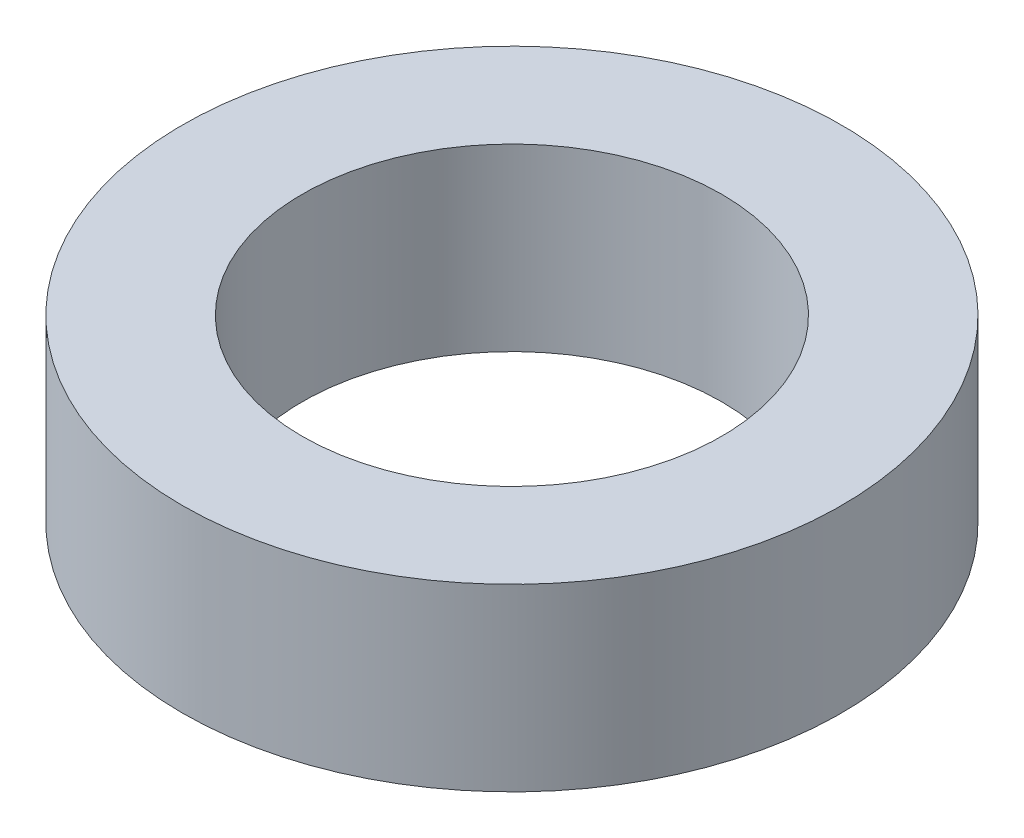
SolidWorks part; units mm, degrees
ref_plane "Front Plane" through (0, 0, 0) normal (0, 0, 1) x (1, 0, 0)
ref_plane "Top Plane" through (0, 0, 0) normal (0, 1, 0) x (1, 0, 0)
ref_plane "Right Plane" through (0, 0, 0) normal (1, 0, 0) x (0, 0, -1)
sketch "Sketch1" plane through (0, 0, 0) normal (0, 1, 0) x (1, 0, 0)
  circle A0 centre (0, 0) radius 5.5
  circle A1 centre (0, 0) radius 3.5
  dimension "D1" = 11
  dimension "D2" = 7
extrude "Boss-Extrude1" add sketch "Sketch1" along normal blind 3
